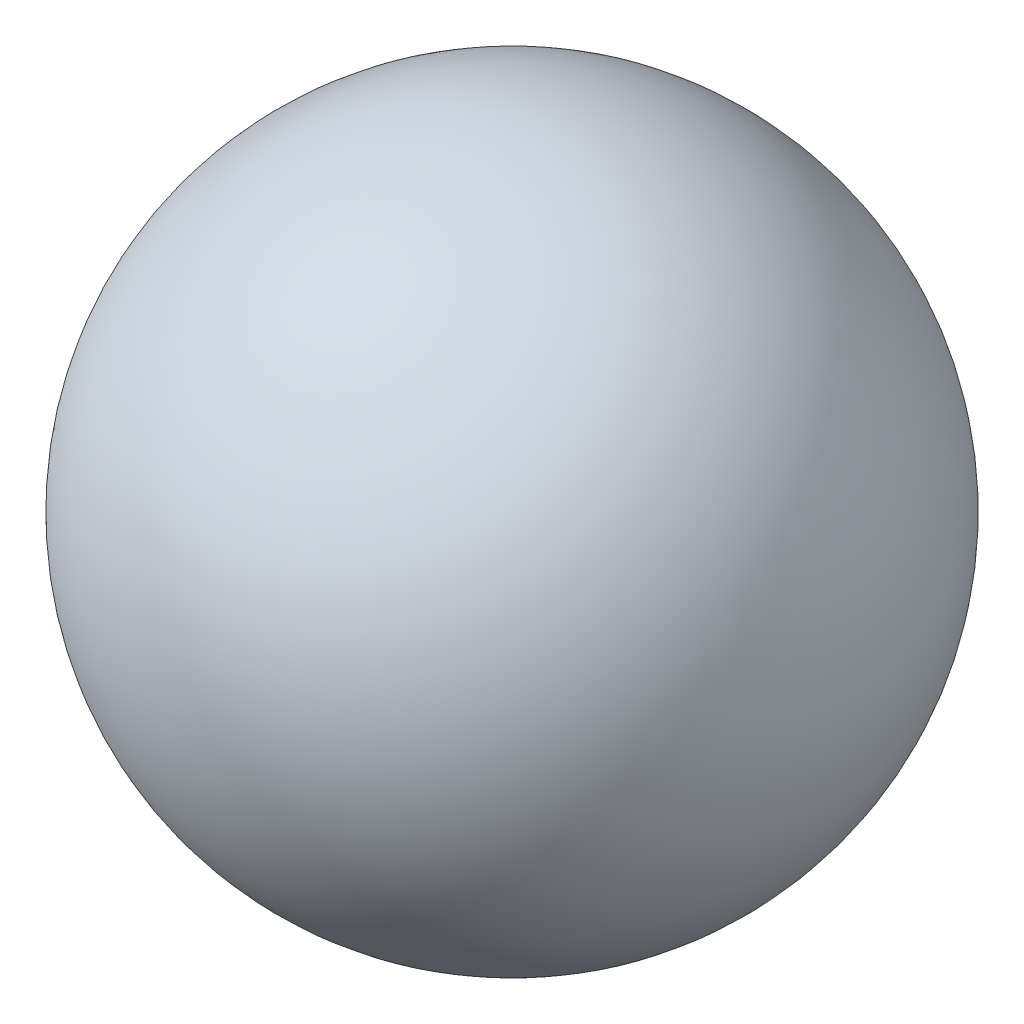
SolidWorks part; units mm, degrees
ref_plane "Front" through (0, 0, 0) normal (0, 0, 1) x (1, 0, 0)
ref_plane "Top" through (0, 0, 0) normal (0, 1, 0) x (1, 0, 0)
ref_plane "Right" through (0, 0, 0) normal (1, 0, 0) x (0, 0, -1)
sketch "Sketch1" plane through (0, 0, 0) normal (0, 0, 1) x (1, 0, 0)
  line L0 (0, 0) -> (0, -83.5154) construction
  line L1 (0, 0) -> (0, -63)
  arc A0 (0, 0) -> (0, -63) centre (0, -31.5) cw
  dimension "D1" = 31.5
  dimension "D2" = 63
revolve "Revolve1" add sketch "Sketch1" angle 360 about L0
